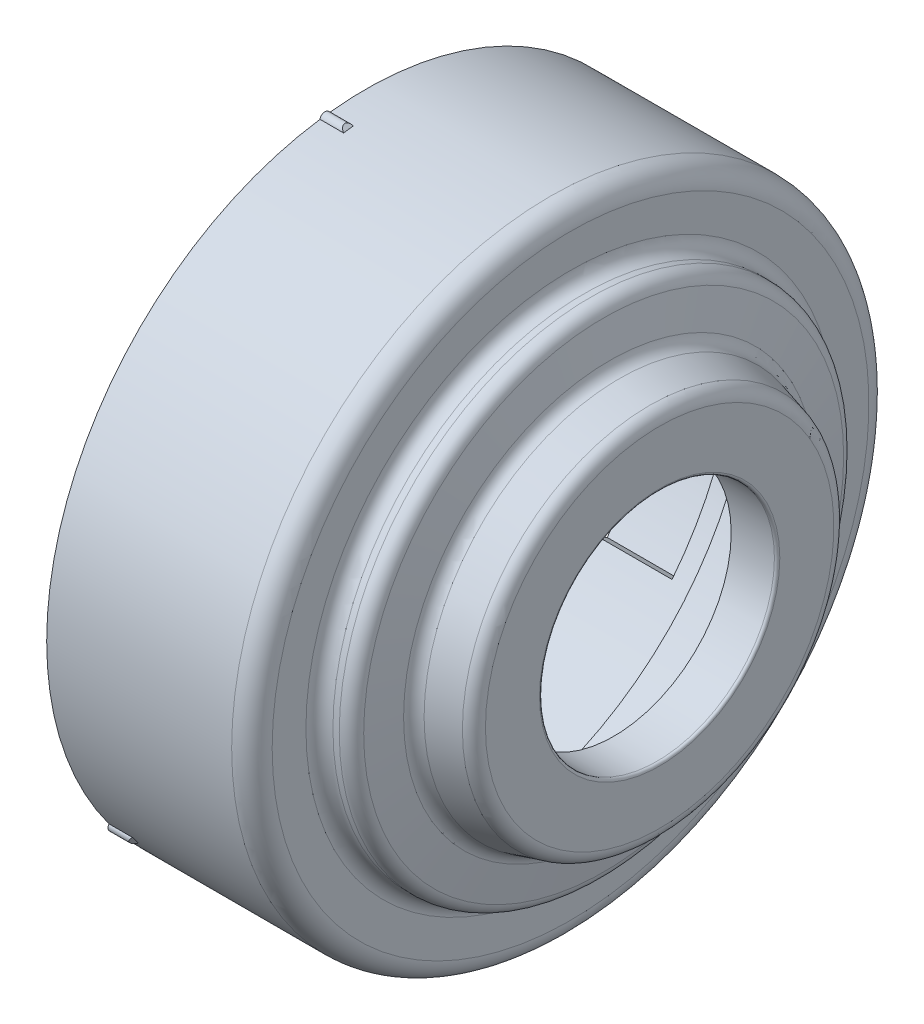
SolidWorks part; units mm, degrees
ref_plane "前视基准面" through (0, 0, 0) normal (0, 0, 1) x (1, 0, 0)
ref_plane "上视基准面" through (0, 0, 0) normal (0, 1, 0) x (1, 0, 0)
ref_plane "右视基准面" through (0, 0, 0) normal (1, 0, 0) x (0, 0, -1)
sketch "草图2" plane through (0, 0, 0) normal (0, 0, 1) x (1, 0, 0)
  line L0 (-36.9366, 0) -> (44.5849, 0) construction
  line L1 (0, 36.0368) -> (0, -37.1166) construction
  line L2 (-14, 22) -> (-6.9, 22)
  line L3 (-6.9, 22) -> (-6.9, 21.6)
  line L4 (-6.9, 21.6) -> (0, 21.6)
  line L5 (0, 21.6) -> (0, 17.4)
  line L6 (0, 17.4) -> (2.5, 17.4)
  line L9 (6.6, 12.75) -> (6.6, 9.4)
  line L10 (6.6, 9.4) -> (4.4, 9.4)
  line L11 (4.4, 9.4) -> (4.4, 8.7)
  line L12 (4.4, 8.7) -> (7.8, 8.7)
  line L13 (-14, 22) -> (-14, 23.6)
  line L14 (-14, 23.6) -> (1.2, 23.6)
  line L15 (1.2, 23.6) -> (1.2, 18.6)
  line L16 (1.2, 18.6) -> (3.5069, 18.6)
  line L19 (7.8, 13.6708) -> (7.8, 8.7)
  line L20 (2.5, 17.4) -> (3.1573, 13.6725)
  line L21 (3.5069, 18.6) -> (4.2063, 14.6337)
  line L22 (6.6, 12.75) -> (3.1573, 13.6725)
  line L23 (7.8, 13.6708) -> (4.2063, 14.6337)
  dimension "D1" = 44
  dimension "D2" = 0.4
  dimension "D3" = 7.1
  dimension "D4" = 14
  dimension "D5" = 34.8
  dimension "D6" = 2.5
  dimension "D7" = 18.8
  dimension "D8" = 0.7
  dimension "D9" = 4.4
  dimension "D10" = 2.2
  dimension "D11" = 25.5
  dimension "D12" = 47.2
  dimension "D13" = 2
  dimension "D14" = 1.2
  dimension "D15" = 10
  dimension "D16" = 105
  dimension "D17" = 1.2
  dimension "D18" = 1.2
  dimension "D19" = 1.2
  dimension "D20" = 1.6
  dimension "D21" = 1.2
revolve "旋转1" add sketch "草图2" angle 360 about L0
fillet "圆角1" radius 0.2 5 edges at (0, 0, 17.4) (0, 0, 21.6) (7.8, 0, 8.7) (2.5, 0, 17.4) (6.6, 0, 12.75)
fillet "圆角2" radius 1 4 edges at (1.2, 0, 18.6) (3.5069, 0, 18.6) (7.8, 0, 13.6708) (4.2063, 0, 14.6337)
fillet "圆角3" radius 1.5 2 edges at (1.2, 0, 23.6) (3.1573, 0, 13.6725)
sketch "草图3" plane through (-14, 0, 0) normal (-1, 0, 0) x (0, 0, 1)
  line L0 (0, 27.1942) -> (0, -25.474) construction
  line L1 (-27.7353, 0) -> (28.2343, 0) construction
  line L2 (-0.5, 22.6) -> (0.5, 22.6)
  line L3 (-0.5, 22.6) -> (-0.5, 21.9943)
  line L4 (0.5, 22.6) -> (0.5, 21.9943)
  circle A0 centre (0, 0) radius 22 construction
  arc A1 (0.5, 21.9943) -> (-0.5, 21.9943) centre (0, 0) ccw
  point P7 (0, 22)
  point P14 (0, 22.6)
  dimension "D1" = 1
  dimension "D2" = 0.6
extrude "切除-拉伸1" cut sketch "草图3" against normal blind 1
sketch "草图4" plane through (-14, 0, 0) normal (-1, 0, 0) x (0, 0, 1)
  line L0 (0, 29.159) -> (0, -31.1439) construction
  line L1 (-35.4917, 0) -> (32.6562, 0) construction
  line L2 (-3.25, 22.5672) -> (-3.25, 21.7586)
  line L3 (3.25, 22.5672) -> (3.25, 21.7586)
  circle A0 centre (0, 0) radius 22 construction
  arc A1 (3.25, 21.7586) -> (-3.25, 21.7586) centre (0, 0) ccw
  arc A2 (3.25, 22.5672) -> (-3.25, 22.5672) centre (0, 0) ccw
  dimension "D2" = 22.8
  dimension "D1" = 6.5
  dimension "D3" = 3.25
extrude "切除-拉伸2" cut sketch "草图4" against normal blind 5.5
sketch "草图5" plane through (0, 0, 0) normal (0, 0, 1) x (1, 0, 0)
  line L0 (16.6242, 0) -> (-23.7431, 0) construction
  line L1 (0, 27.01) -> (0, -27.8633) construction
  line L2 (-8.5, 22.8) -> (-8.5, 21.3419)
  line L3 (-8.5, 21.3419) -> (-10.7, 21.3419)
  line L4 (-10.7, 21.3419) -> (-10.7, 22.8)
  line L5 (-10.7, 22.8) -> (-8.5, 22.8)
  line L7 (-14, -0.1207) -> (-14, 29.419) construction
  line L8 (-14, 21.7586) -> (-14, -22) construction
  dimension "D1" = 3.3
  dimension "D2" = 2.2
  dimension "D3" = 45.6
revolve "切除-旋转1" cut sketch "草图5" angle 24 about L0
ref_plane "基准面1" through (0, 18, 0) normal (0, 1, 0) x (1, 0, 0)
sketch "草图6" plane through (0, 18, 0) normal (0, 1, 0) x (1, 0, 0)
  line L0 (16.0352, 0) -> (-25.287, 0) construction
  line L1 (-10.7, -8.9482) -> (-10.7, -3.25) construction
  line L2 (-10.7, -8.9482) -> (-10.7, -3.25)
  line L3 (-10.7, -3.25) -> (-10.7995, -8.9482)
  line L5 (-10.7, -8.9482) -> (-10.7995, -8.9482)
  dimension "D1" = 1
extrude "切除-拉伸3" cut sketch "草图6" along normal up to surface (2.9707 mm away)
pattern_circular "阵列(圆周)1" count 3 over 360 about axis through (0, 0, 0) along (1, 0, 0) of "切除-拉伸2", "切除-旋转1"
sketch "草图9" plane through (-10.7, 0, 0) normal (1, 0, 0) x (0, 0, -1)
  line L0 (-9.2736, 20.8288) -> (-8.9482, 20.098) construction
  line L1 (-8.9482, 20.9707) -> (-8.9482, 20.098) construction
  line L2 (-9.2736, 20.8288) -> (-8.9482, 20.098)
  line L3 (-8.9482, 20.9707) -> (-8.9482, 20.098)
  arc A0 (-8.9482, 20.9707) -> (-9.2736, 20.8288) centre (0, 0) ccw construction
  arc A1 (-8.9482, 20.9707) -> (-9.2736, 20.8288) centre (0, 0) ccw
extrude "切除-拉伸5" cut sketch "草图9" against normal up to surface (0.0995 mm away)
pattern_circular "阵列(圆周)3" count 3 over 360 about axis through (0, 0, 0) along (1, 0, 0) of "切除-拉伸3"
sketch "草图10" plane through (-10.7, 0, 0) normal (1, 0, 0) x (0, 0, -1)
  line L2 (22.6751, -2.3832) -> (21.8795, -2.2996)
  line L3 (21.8795, -2.2996) -> (22.6352, -2.736)
  line L4 (22.6751, -2.3832) -> (21.8795, -2.2996)
  line L5 (21.8795, -2.2996) -> (22.6352, -2.736)
  arc A1 (22.6352, -2.736) -> (22.6751, -2.3832) centre (0, 0) ccw
  arc A2 (22.6352, -2.736) -> (22.6751, -2.3832) centre (0, 0) ccw
  dimension "D1" = 0
extrude "切除-拉伸6" cut sketch "草图10" against normal up to surface (0.0995 mm away)
sketch "草图11" plane through (-10.7, 0, 0) normal (1, 0, 0) x (0, 0, -1)
  line L2 (-13.4015, -18.4456) -> (-12.9313, -17.7984)
  line L3 (-12.9313, -17.7984) -> (-13.687, -18.2347)
  line L4 (-13.4015, -18.4456) -> (-12.9313, -17.7984)
  line L5 (-12.9313, -17.7984) -> (-13.687, -18.2347)
  arc A1 (-13.687, -18.2347) -> (-13.4015, -18.4456) centre (0, 0) ccw
  arc A2 (-13.687, -18.2347) -> (-13.4015, -18.4456) centre (0, 0) ccw
  dimension "D1" = 0
extrude "切除-拉伸7" cut sketch "草图11" against normal up to surface (0.0995 mm away)
sketch "草图14" plane through (-14, 0, 0) normal (-1, 0, 0) x (0, 0, 1)
  line L0 (0, 28.5305) -> (0, -26.4521) construction
  line L1 (-28.5814, 0) -> (29.2627, 0) construction
  line L3 (0, 0) -> (3.1116, 24.279) construction
  circle A4 centre (0, 0) radius 23.6 construction
  arc A5 (3.3582, 23.3599) -> (2.6411, 23.4517) centre (0, 0) ccw
  arc A6 (3.3582, 23.3599) -> (2.6411, 23.4517) centre (2.9847, 23.2895) ccw
  point P7 (3, 23.4085)
  point P9 (2.9847, 23.2895)
  dimension "D4" = 0.7229
  dimension "D3" = 0.76
  dimension "D1" = 3
  dimension "D2" = 0.12
  dimension "D5" = 7.303
extrude "凸台-拉伸2" add sketch "草图14" against normal blind 1.75
pattern_circular "阵列(圆周)7" count 3 over 360 about axis through (0, 0, 0) along (1, 0, 0) of "凸台-拉伸2"
ref_axis "基准轴1" through (0, 0, 0) along (-1, 0, 0)
ref_plane "基准面2" through (0, 0, 0) normal (0, 0.1271, -0.9919) x (-1, 0, 0)
sketch "草图15" plane through (0, 0, 0) normal (0, 0.1271, -0.9919) x (-1, 0, 0)
  line L0 (12.25, 23.6) -> (12.25, 23.9631)
  line L1 (12.25, 23.9631) -> (12.6131, 23.9631)
  line L2 (12.6131, 23.9631) -> (12.25, 23.6)
  dimension "D1" = 45
revolve "切除-旋转2" cut sketch "草图15" angle 360 about axis through (0, 0, 0) along (-1, 0, 0)
